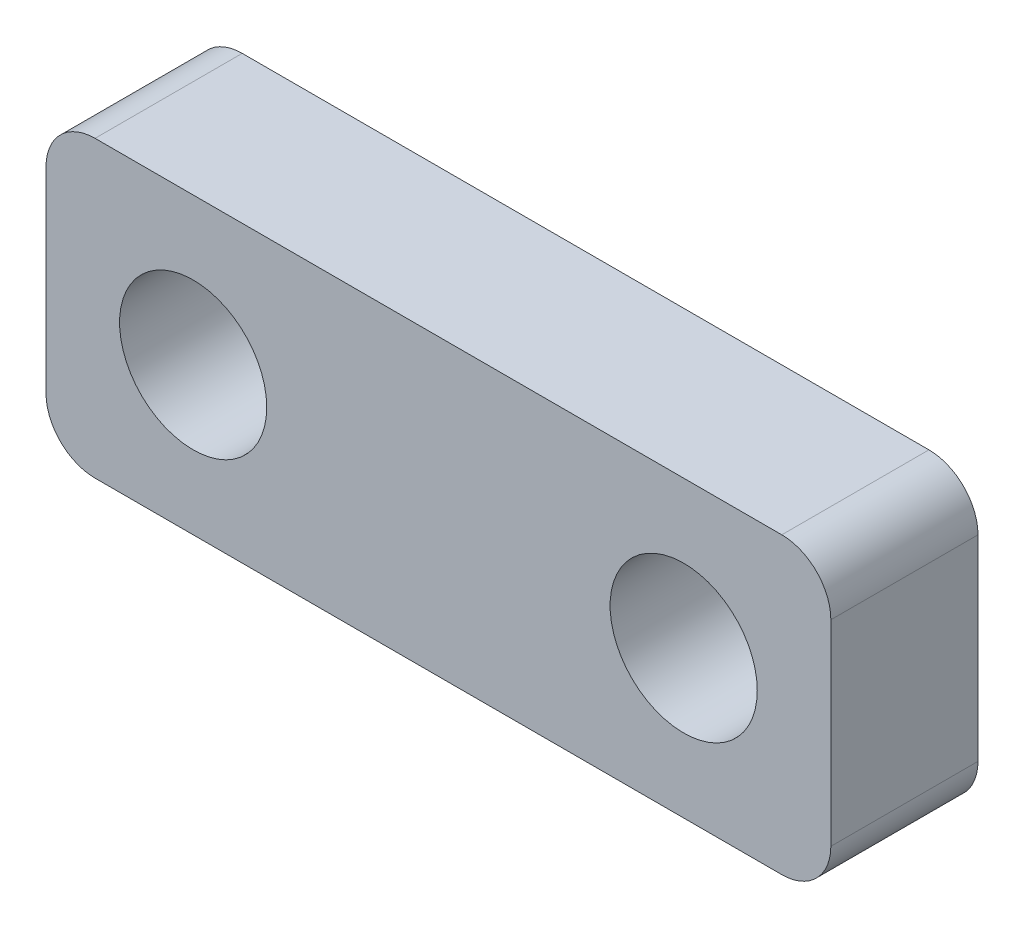
SolidWorks part; units mm, degrees
material "45"
ref_plane "前视基准面" through (0, 0, 0) normal (0, 0, 1) x (1, 0, 0)
ref_plane "上视基准面" through (0, 0, 0) normal (0, 1, 0) x (1, 0, 0)
ref_plane "右视基准面" through (0, 0, 0) normal (1, 0, 0) x (0, 0, -1)
other "Configuration Table"
sketch "草图1" plane through (0, 0, 0) normal (0, 0, 1) x (1, 0, 0)
  line L1 (-8, 3) -> (8, 3)
  line L2 (-8, 3) -> (-8, -3)
  line L3 (-8, -3) -> (8, -3)
  line L4 (8, 3) -> (8, -3)
  line L5 (-8, 3) -> (8, -3) construction
  line L6 (-8, -3) -> (8, 3) construction
  point P0 (0, 0)
  dimension "D1" = 6
  dimension "D2" = 16
extrude "凸台-拉伸1" add sketch "草图1" along normal blind 3
sketch "草图2" plane through (0, 0, 3) normal (0, 0, 1) x (1, 0, 0)
  line L0 (-9.6184, 0) -> (9.6733, 0) construction
  line L1 (8, 3) -> (-8, 3) construction
  line L2 (-5, 4.4611) -> (-5, -3.8382) construction
  line L3 (5, 4.4611) -> (5, -4.114) construction
  circle A0 centre (-5, 0) radius 1.5
  circle A1 centre (5, 0) radius 1.5
  dimension "D4" = 3
  dimension "D5" = 3
  dimension "D1" = 3
  dimension "D2" = 5
  dimension "D3" = 10
extrude "切除-拉伸1" cut sketch "草图2" against normal through all
fillet "圆角1" radius 1 4 edges at (-8, 3, 1.5) (8, 3, 1.5) (8, -3, 1.5) (-8, -3, 1.5)
